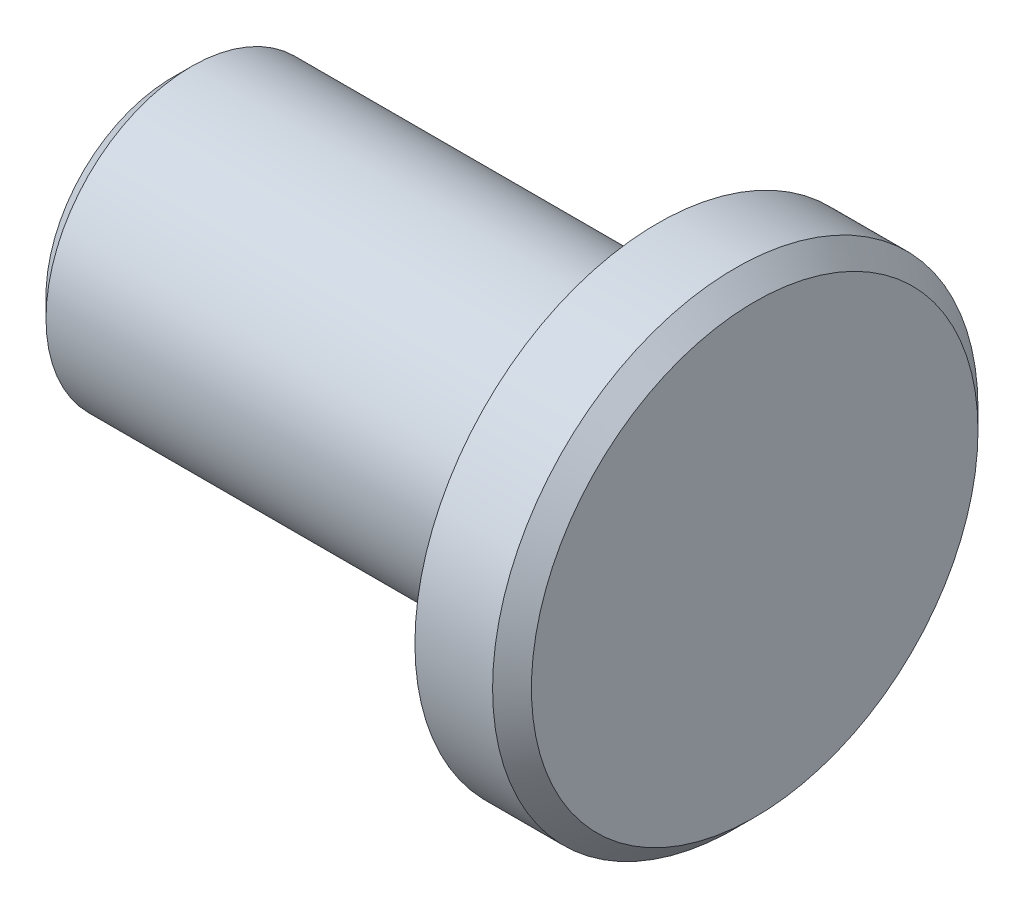
SolidWorks part; units mm, degrees
ref_plane "Front Plane" through (0, 0, 0) normal (0, 0, 1) x (1, 0, 0)
ref_plane "Top Plane" through (0, 0, 0) normal (0, 1, 0) x (1, 0, 0)
ref_plane "Right Plane" through (0, 0, 0) normal (1, 0, 0) x (0, 0, -1)
sketch "Sketch1" plane through (0, 0, 0) normal (1, 0, 0) x (0, 0, -1)
  circle A0 centre (0, 0) radius 1.5
  dimension "D1" = 3
extrude "Boss-Extrude1" add sketch "Sketch1" along normal blind 5
sketch "Sketch2" plane through (5, 0, 0) normal (1, 0, 0) x (0, 0, -1)
  circle A0 centre (0, 0) radius 2.5
  dimension "D1" = 5
extrude "Boss-Extrude2" add sketch "Sketch2" along normal blind 1
chamfer "Chamfer1" distance 0.2 angle 45 2 edges at (0, 0, -1.5) (6, 0, -2.5)
